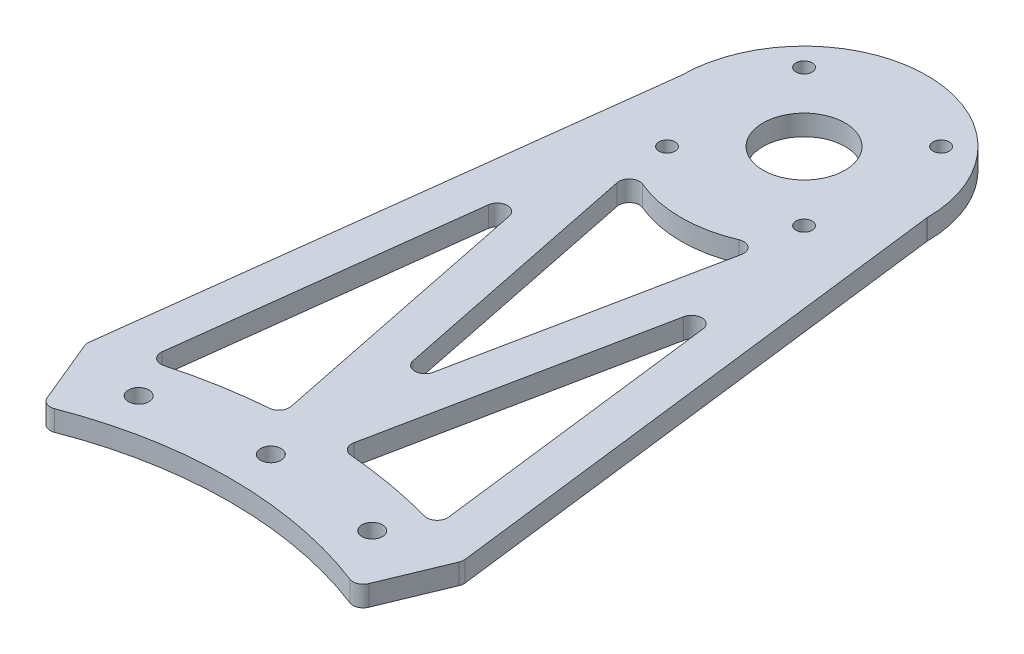
SolidWorks part; units mm, degrees
material "Acrylic (Medium-high impact)"
ref_plane "Front Plane" through (0, 0, 0) normal (0, 0, 1) x (1, 0, 0)
ref_plane "Top Plane" through (0, 0, 0) normal (0, 1, 0) x (1, 0, 0)
ref_plane "Right Plane" through (0, 0, 0) normal (1, 0, 0) x (0, 0, -1)
sketch "Sketch1" plane through (0, 0, 0) normal (0, 1, 0) x (1, 0, 0)
  line L0 (-19.0617, 152.3052) -> (-29.1093, 70.8149)
  line L2 (19.0617, 152.3052) -> (29.1093, 70.8149)
  line L4 (-13.4978, 120.2663) -> (-4.8654, 77.8385)
  line L6 (-9.6268, 133.0897) -> (-1.5556, 93.4205)
  line L7 (-24.9005, 60.1151) -> (-29.0004, 70.0131)
  line L8 (1.5556, 93.4205) -> (9.6268, 133.0897)
  line L9 (24.9005, 60.1151) -> (29.0004, 70.0131)
  line L24 (4.8654, 77.8385) -> (13.4978, 120.2663)
  line L28 (16.629, 120.144) -> (22.1698, 75.2061)
  line L36 (-16.629, 120.144) -> (-22.1698, 75.2061)
  arc A0 (19.0498, 152.4918) -> (-19.0498, 152.4918) centre (0, 152.4) ccw
  arc A1 (22.8623, 59.2416) -> (24.9005, 60.1151) centre (23.4338, 60.7226) ccw
  circle A2 centre (-10.6066, 163.0066) radius 1.25
  circle A3 centre (0, 69.85) radius 1.5875
  circle A4 centre (18.0785, 67.4699) radius 1.5875
  circle A5 centre (10.6066, 163.0066) radius 1.25
  circle A6 centre (10.6066, 141.7934) radius 1.25
  circle A7 centre (0, 152.4) radius 6.35
  arc A10 (20.1739, 73.481) -> (6.29, 75.9399) centre (0, 0) ccw
  arc A12 (-6.29, 75.9399) -> (-20.1739, 73.481) centre (0, 0) ccw
  circle A13 centre (-10.6066, 141.7934) radius 1.25
  arc A22 (22.1698, 75.2061) -> (20.1739, 73.481) centre (20.5942, 75.0118) cw
  circle A26 centre (-18.0785, 67.4699) radius 1.5875
  arc A27 (-22.1698, 75.2061) -> (-20.1739, 73.481) centre (-20.5942, 75.0118) ccw
  arc A28 (4.8654, 77.8385) -> (6.29, 75.9399) centre (6.421, 77.522) ccw
  arc A29 (16.629, 120.144) -> (13.4978, 120.2663) centre (15.0534, 119.9498) ccw
  arc A30 (-16.629, 120.144) -> (-13.4978, 120.2663) centre (-15.0534, 119.9498) cw
  arc A31 (-7.4503, 134.8673) -> (7.4503, 134.8673) centre (0, 152.4) ccw
  arc A32 (-4.8654, 77.8385) -> (-6.29, 75.9399) centre (-6.421, 77.522) cw
  arc A33 (-9.6268, 133.0897) -> (-7.4503, 134.8673) centre (-8.0712, 133.4062) cw
  arc A34 (22.8623, 59.2416) -> (-22.8623, 59.2416) centre (0, 0) ccw
  circle A35 centre (49.3914, 49.3914) radius 1.5875 [skipped]
  circle A36 centre (60.4919, 34.925) radius 1.5875 [skipped]
  circle A37 centre (67.4699, 18.0785) radius 1.5875 [skipped]
  circle A38 centre (69.85, 0) radius 1.5875 [skipped]
  circle A39 centre (67.4699, -18.0785) radius 1.5875 [skipped]
  circle A40 centre (60.4919, -34.925) radius 1.5875 [skipped]
  circle A41 centre (49.3914, -49.3914) radius 1.5875 [skipped]
  circle A42 centre (34.925, -60.4919) radius 1.5875 [skipped]
  circle A43 centre (18.0785, -67.4699) radius 1.5875 [skipped]
  circle A44 centre (0, -69.85) radius 1.5875 [skipped]
  circle A45 centre (-18.0785, -67.4699) radius 1.5875 [skipped]
  circle A46 centre (-34.925, -60.4919) radius 1.5875 [skipped]
  circle A47 centre (-49.3914, -49.3914) radius 1.5875 [skipped]
  circle A48 centre (-60.4919, -34.925) radius 1.5875 [skipped]
  circle A49 centre (-67.4699, -18.0785) radius 1.5875 [skipped]
  circle A50 centre (-69.85, 0) radius 1.5875 [skipped]
  circle A51 centre (-67.4699, 18.0785) radius 1.5875 [skipped]
  circle A52 centre (-60.4919, 34.925) radius 1.5875 [skipped]
  circle A53 centre (-49.3914, 49.3914) radius 1.5875 [skipped]
  circle A54 centre (-34.925, 60.4919) radius 1.5875 [skipped]
  circle A55 centre (34.925, 60.4919) radius 1.5875 [skipped]
  arc A58 (9.6268, 133.0897) -> (7.4503, 134.8673) centre (8.0712, 133.4062) ccw
  arc A59 (-1.5556, 93.4205) -> (1.5556, 93.4205) centre (0, 93.737) ccw
  arc A61 (19.0617, 152.3052) -> (19.0498, 152.4918) centre (20.6373, 152.4994) cw
  arc A62 (29.0004, 70.0131) -> (29.1093, 70.8149) centre (27.5337, 70.6206) ccw
  arc A63 (-29.1093, 70.8149) -> (-29.0004, 70.0131) centre (-27.5337, 70.6206) ccw
  arc A64 (-24.9005, 60.1151) -> (-22.8623, 59.2416) centre (-23.4338, 60.7226) ccw
  arc A65 (-19.0617, 152.3052) -> (-19.0498, 152.4918) centre (-20.6373, 152.4994) ccw
  point P34 (10.9402, 145.95)
  point P56 (0, 0)
  point P71 (0, 0)
  point P134 (-4.5049, 76.0667)
  point P145 (19.05, 152.4)
  dimension "D1" = 4
  dimension "D2" = 1.5875
extrude "Boss-Extrude1" add sketch "Sketch1" along normal blind 3.175
